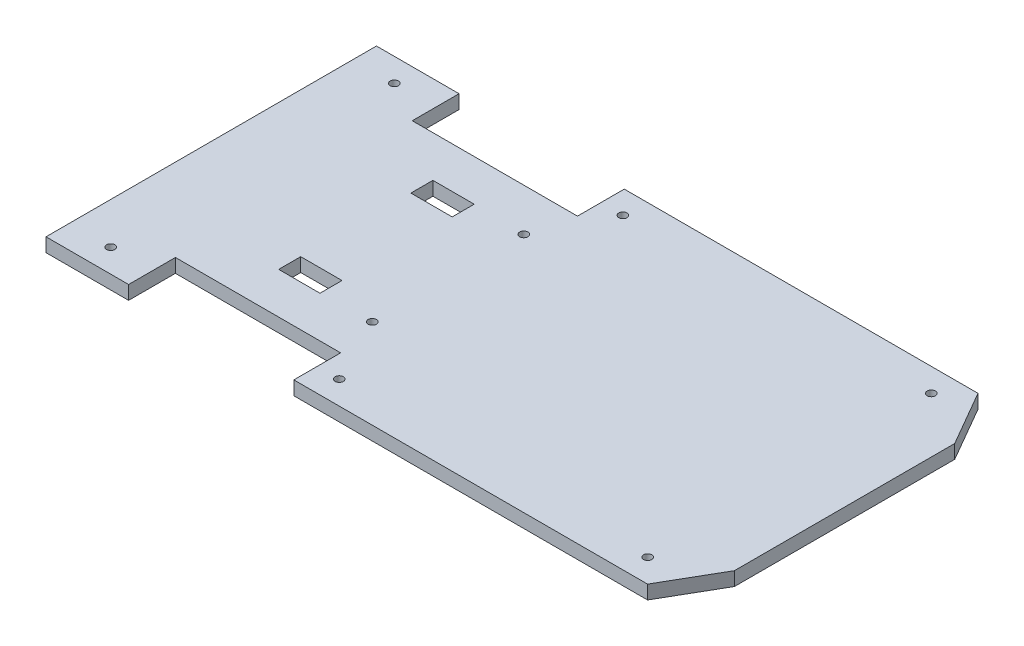
SolidWorks part; units mm, degrees
ref_plane "Plan de face" through (0, 0, 0) normal (0, 0, 1) x (1, 0, 0)
ref_plane "Plan de dessus" through (0, 0, 0) normal (0, 1, 0) x (1, 0, 0)
ref_plane "Plan de droite" through (0, 0, 0) normal (1, 0, 0) x (0, 0, -1)
sketch "Esquisse1" plane through (0, 0, 0) normal (0, 1, 0) x (1, 0, 0)
  line L0 (103.453, 60) -> (115, 40)
  line L1 (-115, 0) -> (115, 0)
  line L2 (-115, 0) -> (-115, 60)
  line L3 (-115, 60) -> (-85, 60)
  line L4 (115, 0) -> (115, 40)
  line L5 (-85, 60) -> (-85, 43)
  line L6 (-85, 43) -> (-25, 43)
  line L7 (-25, 43) -> (-25, 60)
  line L8 (-25, 60) -> (103.453, 60)
  line L9 (-85, 51.5) -> (-115, 51.5) construction
  line L10 (-62.5, 28) -> (-47.5, 28)
  line L11 (-62.5, 28) -> (-62.5, 20)
  line L12 (-62.5, 20) -> (-47.5, 20)
  line L13 (-47.5, 28) -> (-47.5, 20)
  circle A0 centre (-100, 51.5) radius 1.5
  circle A1 centre (-17, 51.5) radius 1.5
  circle A2 centre (95, 51.5) radius 1.5
  circle A3 centre (-29, 27.5) radius 1.5
  point P8 (-55, 43)
  point P15 (-55, 28)
  point P21 (-100, 60)
  point P26 (-25, 51.5)
  dimension "D11" = 3
  dimension "D14" = 15.5
  dimension "D1" = 60
  dimension "D2" = 230
  dimension "D3" = 120
  dimension "D4" = 40
  dimension "D5" = 60
  dimension "D6" = 17
  dimension "D7" = 170
  dimension "D8" = 15
  dimension "D9" = 8
  dimension "D10" = 15
  dimension "D12" = 8
  dimension "D13" = 20
  dimension "D15" = 4
extrude "Boss.-Extru.1" add sketch "Esquisse1" along normal blind 5
mirror "Symétrie1" about plane through (-115, 5, 0) normal (0, 0, -1) of "Boss.-Extru.1"
